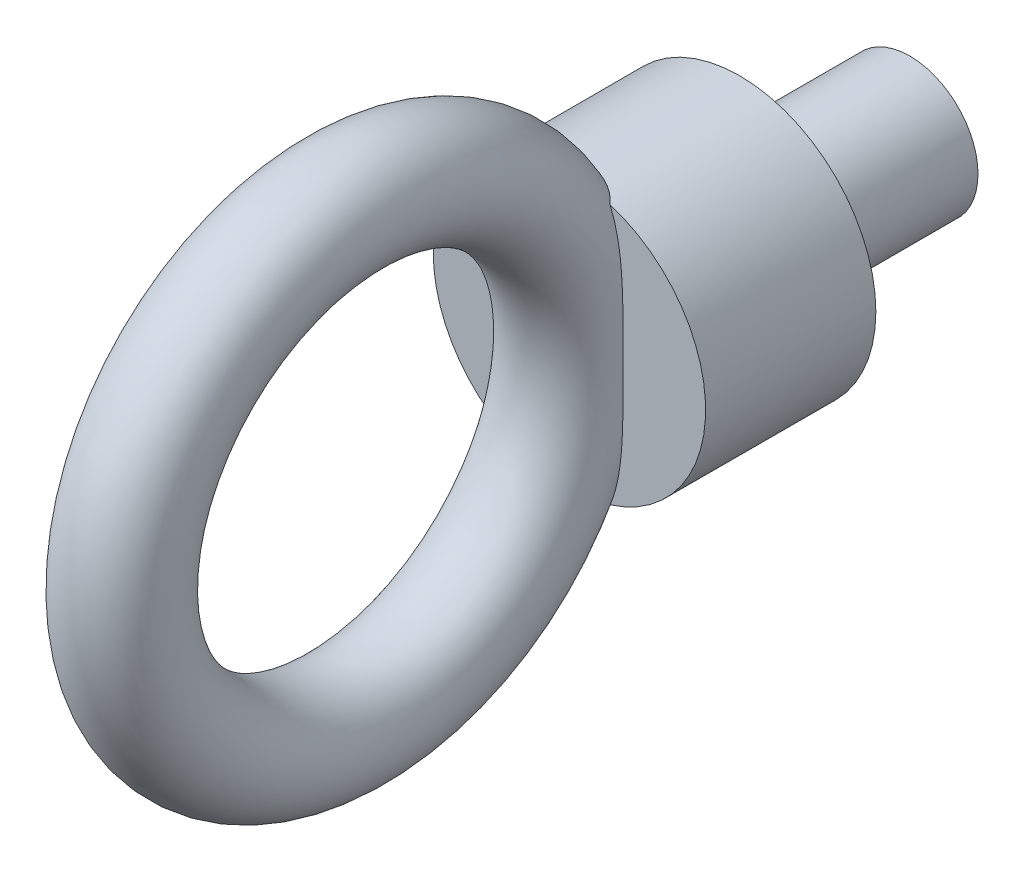
SolidWorks part; units mm, degrees
ref_plane "正面" through (0, 0, 0) normal (0, 0, 1) x (1, 0, 0)
ref_plane "平面" through (0, 0, 0) normal (0, 1, 0) x (1, 0, 0)
ref_plane "右側面" through (0, 0, 0) normal (1, 0, 0) x (0, 0, -1)
sketch "ｽｹｯﾁ1" plane through (0, 0, 0) normal (0, 0, 1) x (1, 0, 0)
  circle A0 centre (0, 0) radius 4
  dimension "D1" = 8
extrude "ﾎﾞｽ - 押し出し1" add sketch "ｽｹｯﾁ1" along normal blind 20
cosmetic thread "ねじ山1" parameters "D1"=15, "D2"=6.619
sketch "ｽｹｯﾁ2" plane through (0, 0, 0) normal (0, 1, 0) x (1, 0, 0)
  line L0 (-4, -20) -> (4, -20) construction
  line L1 (-4, -20) -> (4, -20)
  circle A0 centre (0, -20) radius 3.15
  dimension "D1" = 6.3
sketch "ｽｹｯﾁ3" plane through (0, 0, 0) normal (1, 0, 0) x (0, 0, -1)
  line L0 (-20, 4) -> (-20, -4) construction
  line L1 (-20, 4) -> (-20, -4)
  circle A0 centre (-33.15, 0) radius 13.15
  dimension "D1" = 26.3
sweep "ｽｲｰﾌﾟ1" add profiles "ｽｹｯﾁ2" path "ｽｹｯﾁ3"
ref_plane "平面1" through (0, 0, 15) normal (0, 0, -1) x (-1, 0, 0)
sketch "ｽｹｯﾁ4" plane through (0, 0, 15) normal (0, 0, -1) x (-1, 0, 0)
  circle A0 centre (0, 0) radius 8
  dimension "D1" = 16
extrude "ﾎﾞｽ - 押し出し2" add sketch "ｽｹｯﾁ4" against normal mid plane 10
sketch "ｽｹｯﾁ5" plane through (0, 0, 0) normal (1, 0, 0) x (0, 0, -1)
  point P0 (-42.2764, 0)
